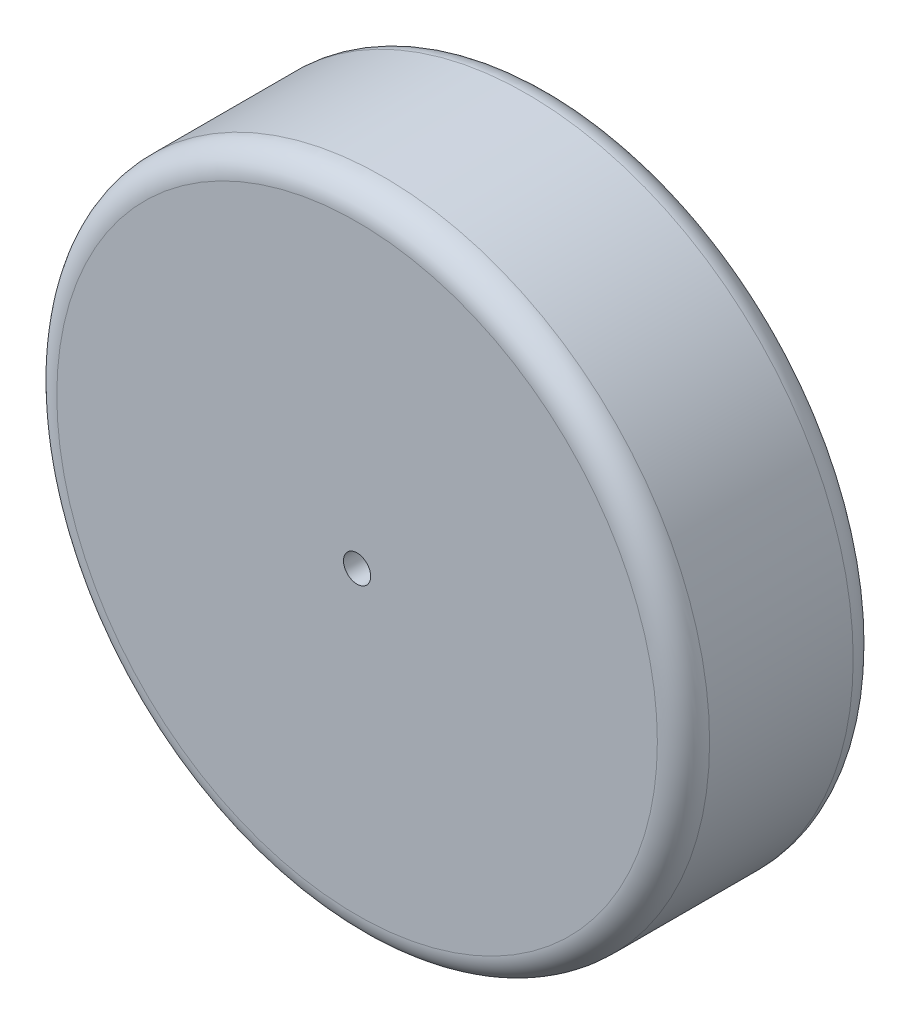
SolidWorks part; units mm, degrees
ref_plane "Front Plane" through (0, 0, 0) normal (0, 0, 1) x (1, 0, 0)
ref_plane "Top Plane" through (0, 0, 0) normal (0, 1, 0) x (1, 0, 0)
ref_plane "Right Plane" through (0, 0, 0) normal (1, 0, 0) x (0, 0, -1)
sketch "Sketch1" plane through (0, 0, 0) normal (0, 0, 1) x (1, 0, 0)
  line L0 (0, 0) -> (0, 25)
  circle A0 centre (0, 0) radius 25
  dimension "D1" = 50
extrude "Boss-Extrude1" add sketch "Sketch1" along normal blind 15 contours A0
fillet "Fillet1" radius 2 2 edges at (25, 0, 15) (25, 0, 0)
sketch "Sketch7" plane through (0, 0, 15) normal (0, 0, 1) x (1, 0, 0)
  circle A0 centre (0, 0) radius 1.04
extrude "Cut-Extrude2" cut sketch "Sketch7" against normal through all
